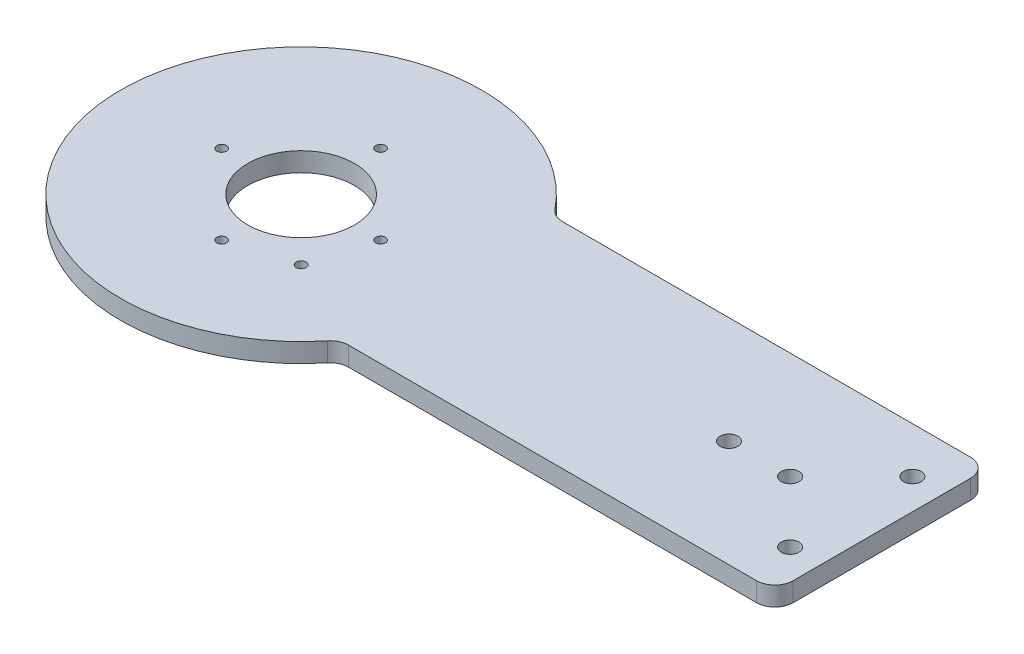
SolidWorks part; units mm, degrees
material "Acrylic (Medium-high impact)"
ref_plane "Front" through (0, 0, 0) normal (0, 0, 1) x (1, 0, 0)
ref_plane "Top" through (0, 0, 0) normal (0, 1, 0) x (1, 0, 0)
ref_plane "Right" through (0, 0, 0) normal (1, 0, 0) x (0, 0, -1)
sketch "Sketch1" plane through (0, 0, 0) normal (0, 1, 0) x (1, 0, 0)
  line L0 (228.6, 0) -> (0, 0) construction
  line L1 (241.3, -44.45) -> (60.41, -44.45)
  line L2 (241.3, 44.45) -> (60.41, 44.45)
  line L3 (241.3, 44.45) -> (241.3, -44.45)
  circle A2 centre (0, 0) radius 21.9583 construction
  arc A4 (60.41, 44.45) -> (60.41, -44.45) centre (0, 0) ccw
  point P3 (0, 0)
  dimension "D1" = 228.6
  dimension "D3" = 43.9166
  dimension "D4" = 44.45
  dimension "D5" = 75.0011
  dimension "D2" = 88.9
  dimension "D6" = 12.7
extrude "Boss-Extrude1" add sketch "Sketch1" along normal blind 7.9375
sketch "Sketch21" plane through (0, 7.9375, 0) normal (0, 1, 0) x (1, 0, 0)
  circle A0 centre (0, 0) radius 22.1615
  circle A1 centre (0, 0) radius 33.02 construction
  circle A2 centre (0, 33.02) radius 2.0193
  circle A3 centre (-33.02, 0) radius 2.0193
  circle A4 centre (0, -33.02) radius 2.0193
  circle A5 centre (33.02, 0) radius 2.0193
  circle A6 centre (25.4, -25.4) radius 2.0193
  dimension "D1" = 44.323
  dimension "D5" = 4.0386
  dimension "D2" = 25.4
  dimension "D3" = 25.4
  dimension "D4" = 33.02
extrude "Cut-Extrude2" cut sketch "Sketch21" against normal through all
fillet "Fillet1" radius 7.62 4 edges at (60.41, 3.9688, 44.45) (60.41, 3.9688, -44.45) (241.3, 3.9688, 44.45) (241.3, 3.9688, -44.45)
hole_wizard "L (0.29) Diameter Hole1" positions "Sketch17" profile "Sketch18" hole size "L" standard "ANSI Inch" end condition through all
sketch "Sketch17" plane through (0, 7.9375, 0) normal (0, 1, 0) x (1, 0, 0)
  line L0 (228.6, -25.4) -> (228.6, 25.4) construction
  line L1 (241.3, -36.83) -> (241.3, 36.83) construction
  point P0 (228.6, 25.4)
  point P2 (228.6, -25.4)
  point P27 (203.2, 0)
  point P35 (177.8, 0)
  dimension "D1" = 12.7
  dimension "D2" = 50.8
  dimension "D3" = 25.4
  dimension "D4" = 25.4
sketch "Sketch18" plane through (228.6, 7.9375, -25.4) normal (1, 0, 0) x (0, 0, 1)
  line L0 (0, 0) -> (0, 7.9375)
  line L1 (0, 7.9375) -> (3.683, 7.9375)
  line L2 (3.683, 7.9375) -> (3.683, 0)
  line L5 (3.683, 0) -> (0, 0)
  line L11 (0, -6.35) -> (0, 107.95) construction
  dimension "Thru Hole Dia." = 7.366
  dimension "Thru Hole Depth" = 7.9375
